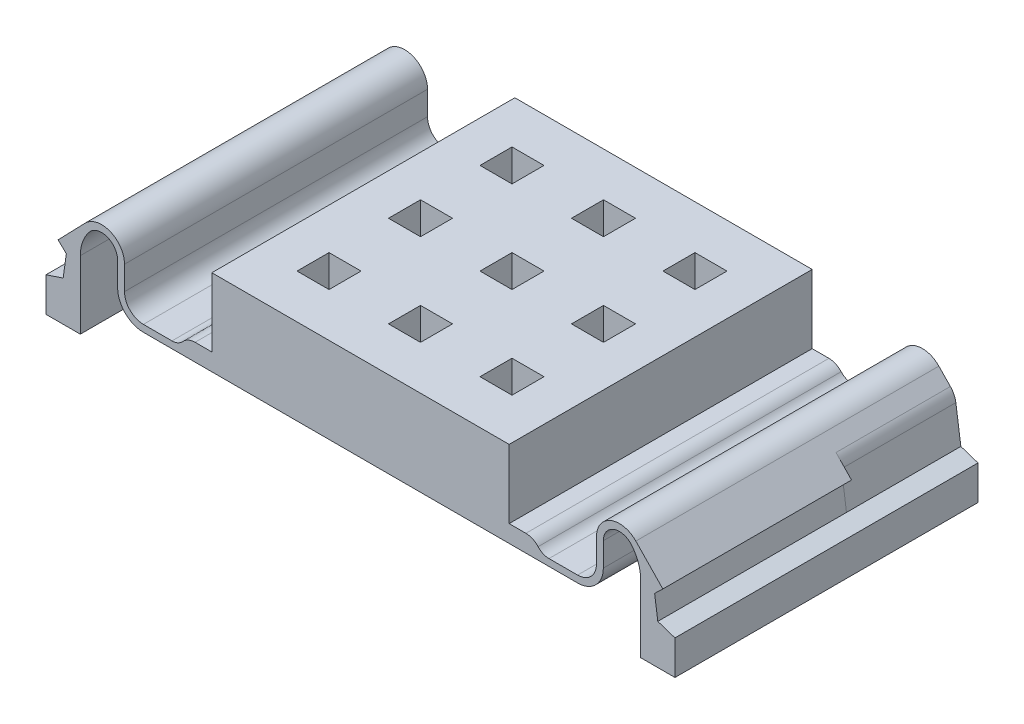
SolidWorks part; units mm, degrees
ref_plane "Plano frontal" through (0, 0, 0) normal (0, 0, 1) x (1, 0, 0)
ref_plane "Plano superior" through (0, 0, 0) normal (0, 1, 0) x (1, 0, 0)
ref_plane "Plano direito" through (0, 0, 0) normal (1, 0, 0) x (0, 0, -1)
sketch "Esboço3" plane through (0, 0, 0) normal (0, 0, 1) x (1, 0, 0)
  line L0 (35.3553, 11.1741) -> (52.3259, 28.1447) construction
  line L1 (-52.3259, 28.1447) -> (-35.3553, 11.1741) construction
  line L2 (-29.6985, 5.5172) -> (-26.0746, 1.8933) construction
  line L3 (-26.0746, 1.8933) -> (-24.9255, 9.9367) construction
  line L4 (-24.9255, 9.9367) -> (-25.1023, 10.1134) construction
  line L5 (-25.1023, 10.1134) -> (-29.6985, 5.5172) construction
  line L6 (25.1023, 10.1134) -> (24.9255, 9.9367) construction
  line L7 (24.9255, 9.9367) -> (26.0746, 1.8933) construction
  line L8 (26.0746, 1.8933) -> (29.6985, 5.5172) construction
  line L9 (29.6985, 5.5172) -> (25.1023, 10.1134) construction
  line L10 (63.1459, 37.2499) -> (26.001, 0) construction
  line L11 (-26.3397, 0.0372) -> (-63.4628, 37.1603) construction
  line L12 (26.3397, 0.0372) -> (24.9255, 9.9367) construction
  line L13 (-24.9255, 9.9367) -> (-26.3397, 0.0372) construction
  line L14 (18.9851, -0.6) -> (-18.9831, -0.6)
  line L15 (26.001, 0) -> (25.7227, 1.9805)
  line L16 (25.7227, 1.9805) -> (26.442, 2.6752)
  line L17 (26.442, 2.6752) -> (24.0804, 5.1207)
  line L18 (20.6376, 3.7297) -> (20.6376, 1.6525)
  line L19 (26.001, 0) -> (26.001, -1.5)
  line L20 (26.001, -1.5) -> (24.501, -1.5)
  line L21 (21.2376, 3.7297) -> (21.2376, 1.6525)
  line L22 (0.001, -0.6) -> (0.001, 0.9045) construction
  line L23 (24.501, -1.5) -> (24.501, 2.4453)
  line L24 (-7.2663, 0.9045) -> (7.2683, 0.9045)
  line L25 (18.9851, 0) -> (16.4851, 0)
  line L26 (0.001, -0.6) -> (18.9851, -0.6) construction
  line L27 (25.401, -0.042) -> (25.401, -1.5) construction
  line L28 (25.401, -0.042) -> (25.0859, 2.1998) construction
  line L29 (25.0859, 2.1998) -> (25.5936, 2.69) construction
  line L30 (25.5936, 2.69) -> (23.6488, 4.7039) construction
  line L31 (0.001, 0) -> (18.9851, 0) construction
  line L32 (7.2683, 0.9045) -> (14.4666, 0.9045)
  line L33 (-7.2663, 0.9045) -> (-14.4646, 0.9045)
  line L34 (-18.9831, 0) -> (-16.4831, 0)
  line L35 (-24.499, -1.5) -> (-24.499, 2.4453)
  line L36 (-21.2356, 3.7297) -> (-21.2356, 1.6525)
  line L37 (-25.999, -1.5) -> (-24.499, -1.5)
  line L38 (-25.999, 0) -> (-25.999, -1.5)
  line L39 (-20.6356, 3.7297) -> (-20.6356, 1.6525)
  line L40 (-26.44, 2.6752) -> (-24.0784, 5.1207)
  line L41 (-25.7207, 1.9805) -> (-26.44, 2.6752)
  line L42 (-25.999, 0) -> (-25.7207, 1.9805)
  arc A0 (24.0804, 5.1207) -> (20.6376, 3.7297) centre (22.64, 3.7297) ccw
  arc A1 (18.9851, 0) -> (20.6376, 1.6525) centre (18.9851, 1.6525) ccw
  arc A2 (18.9851, -0.6) -> (21.2376, 1.6525) centre (18.9851, 1.6525) ccw
  arc A3 (23.6488, 4.7039) -> (21.2376, 3.7297) centre (22.64, 3.7297) ccw
  arc A4 (24.501, 2.4453) -> (23.6488, 4.7039) centre (21.082, 2.4453) ccw
  arc A5 (16.4851, 0) -> (15.5348, 0.4259) centre (16.4851, 1.2733) cw
  arc A6 (15.5348, 0.4259) -> (14.4666, 0.9045) centre (14.4666, -0.5266) ccw
  arc A7 (-15.5328, 0.4259) -> (-14.4646, 0.9045) centre (-14.4646, -0.5266) cw
  arc A8 (-16.4831, 0) -> (-15.5328, 0.4259) centre (-16.4831, 1.2733) ccw
  arc A9 (-24.499, 2.4453) -> (-23.6468, 4.7039) centre (-21.08, 2.4453) cw
  arc A10 (-23.6468, 4.7039) -> (-21.2356, 3.7297) centre (-22.638, 3.7297) cw
  arc A11 (-18.9831, -0.6) -> (-21.2356, 1.6525) centre (-18.9831, 1.6525) cw
  arc A12 (-18.9831, 0) -> (-20.6356, 1.6525) centre (-18.9831, 1.6525) cw
  arc A13 (-24.0784, 5.1207) -> (-20.6356, 3.7297) centre (-22.638, 3.7297) cw
  dimension "D6" = 0.6
  dimension "D1" = 26
  dimension "D3" = 2
  dimension "D5" = 1
  dimension "D4" = 234
extrude "Ressalto-extrusão1" add sketch "Esboço3" along normal blind 16.5
sketch "Esboço4" plane through (0, -1.5, 0) normal (0, -1, 0) x (1, 0, 0)
  line L0 (24.501, 0) -> (26.001, 0) construction
  line L1 (26.001, 0) -> (26.001, 16.5) construction
  line L2 (26.001, 16.5) -> (24.501, 16.5) construction
  line L3 (24.501, 16.5) -> (24.501, 0) construction
  line L4 (-25.999, 0) -> (-24.499, 0) construction
  line L5 (-24.499, 0) -> (-24.499, 16.5) construction
  line L6 (-24.499, 16.5) -> (-25.999, 16.5) construction
  line L7 (-25.999, 16.5) -> (-25.999, 0) construction
  line L8 (24.501, 0) -> (26.001, 0)
  line L9 (26.001, 0) -> (26.001, 16.5)
  line L10 (26.001, 16.5) -> (24.501, 16.5)
  line L11 (24.501, 16.5) -> (24.501, 0)
  line L12 (-25.999, 0) -> (-24.499, 0)
  line L13 (-24.499, 0) -> (-24.499, 16.5)
  line L14 (-24.499, 16.5) -> (-25.999, 16.5)
  line L15 (-25.999, 16.5) -> (-25.999, 0)
extrude "Ressalto-extrusão2" add sketch "Esboço4" along normal blind 2
sketch "Esboço2" plane through (0, 0, 0) normal (0, 0, 1) x (1, 0, 0)
  line L0 (0.001, 0.9045) -> (0.001, -0.6) construction
  line L1 (14.4666, 0.9045) -> (-14.4646, 0.9045)
  line L2 (18.9851, -0.6) -> (-18.9831, -0.6)
  line L3 (-24.499, -3.5) -> (-25.999, -3.5)
  line L4 (-24.499, 2.4453) -> (-24.499, -3.5)
  line L5 (-21.2356, 1.6525) -> (-21.2356, 3.7297)
  line L6 (-18.9831, 0) -> (-16.4831, 0)
  line L7 (-20.6356, 3.7297) -> (-20.6356, 1.6525)
  line L8 (-25.0829, 4.0805) -> (-24.0784, 5.1207)
  line L9 (-25.999, -3.5) -> (-25.999, 0)
  line L10 (26.001, 0) -> (25.5647, 3.0972)
  line L11 (-25.999, 0) -> (-25.5627, 3.0972)
  line L39 (26.001, -3.5) -> (26.001, 0)
  line L40 (26.001, 0) -> (25.7227, 1.9805)
  line L41 (25.7227, 1.9805) -> (26.442, 2.6752)
  line L42 (26.442, 2.6752) -> (24.0804, 5.1207)
  line L43 (20.6376, 3.7297) -> (20.6376, 1.6525)
  line L44 (18.9851, 0) -> (16.4851, 0)
  line L45 (14.4666, 0.9045) -> (-14.4646, 0.9045)
  line L46 (-16.4831, 0) -> (-18.9831, 0)
  line L47 (-20.6356, 1.6525) -> (-20.6356, 3.7297)
  line L48 (-24.0784, 5.1207) -> (-26.44, 2.6752)
  line L49 (-26.44, 2.6752) -> (-25.7207, 1.9805)
  line L50 (-25.7207, 1.9805) -> (-25.999, 0)
  line L51 (-25.999, 0) -> (-25.999, -3.5)
  line L52 (-25.999, -3.5) -> (-24.499, -3.5)
  line L53 (-24.499, -3.5) -> (-24.499, 2.4453)
  line L54 (-21.2356, 3.7297) -> (-21.2356, 1.6525)
  line L55 (-18.9831, -0.6) -> (18.9851, -0.6)
  line L56 (21.2376, 1.6525) -> (21.2376, 3.7297)
  line L57 (24.501, 2.4453) -> (24.501, -3.5)
  line L58 (24.501, -3.5) -> (26.001, -3.5)
  line L59 (26.001, -3.5) -> (26.001, 0)
  line L62 (25.0849, 4.0805) -> (24.0804, 5.1207)
  line L63 (20.6376, 3.7297) -> (20.6376, 1.6525)
  line L64 (18.9851, 0) -> (16.4851, 0)
  line L76 (21.2376, 1.6525) -> (21.2376, 3.7297)
  line L77 (24.501, 2.4453) -> (24.501, -3.5)
  line L78 (24.501, -3.5) -> (26.001, -3.5)
  arc A0 (25.5647, 3.0972) -> (25.0849, 4.0805) centre (23.8109, 2.8501) ccw
  arc A1 (-24.499, 2.4453) -> (-23.6468, 4.7039) centre (-21.08, 2.4453) cw
  arc A2 (-23.6468, 4.7039) -> (-21.2356, 3.7297) centre (-22.638, 3.7297) cw
  arc A3 (-18.9831, -0.6) -> (-21.2356, 1.6525) centre (-18.9831, 1.6525) cw
  arc A4 (-15.5328, 0.4259) -> (-14.4646, 0.9045) centre (-14.4646, -0.5266) cw
  arc A5 (-15.5328, 0.4259) -> (-16.4831, 0) centre (-16.4831, 1.2733) cw
  arc A6 (-18.9831, 0) -> (-20.6356, 1.6525) centre (-18.9831, 1.6525) cw
  arc A7 (-24.0784, 5.1207) -> (-20.6356, 3.7297) centre (-22.638, 3.7297) cw
  arc A8 (-25.5627, 3.0972) -> (-25.0829, 4.0805) centre (-23.8089, 2.8501) cw
  arc A14 (24.0804, 5.1207) -> (20.6376, 3.7297) centre (22.64, 3.7297) ccw
  arc A15 (18.9851, 0) -> (20.6376, 1.6525) centre (18.9851, 1.6525) ccw
  arc A16 (15.5348, 0.4259) -> (16.4851, 0) centre (16.4851, 1.2733) ccw
  arc A17 (15.5348, 0.4259) -> (14.4666, 0.9045) centre (14.4666, -0.5266) ccw
  arc A18 (-14.4646, 0.9045) -> (-15.5328, 0.4259) centre (-14.4646, -0.5266) ccw
  arc A19 (-16.4831, 0) -> (-15.5328, 0.4259) centre (-16.4831, 1.2733) ccw
  arc A20 (-20.6356, 1.6525) -> (-18.9831, 0) centre (-18.9831, 1.6525) ccw
  arc A21 (-20.6356, 3.7297) -> (-24.0784, 5.1207) centre (-22.638, 3.7297) ccw
  arc A22 (-23.6468, 4.7039) -> (-24.499, 2.4453) centre (-21.08, 2.4453) ccw
  arc A23 (-21.2356, 3.7297) -> (-23.6468, 4.7039) centre (-22.638, 3.7297) ccw
  arc A24 (-21.2356, 1.6525) -> (-18.9831, -0.6) centre (-18.9831, 1.6525) ccw
  arc A25 (18.9851, -0.6) -> (21.2376, 1.6525) centre (18.9851, 1.6525) ccw
  arc A26 (23.6488, 4.7039) -> (21.2376, 3.7297) centre (22.64, 3.7297) ccw
  arc A27 (24.501, 2.4453) -> (23.6488, 4.7039) centre (21.082, 2.4453) ccw
  arc A28 (24.0804, 5.1207) -> (20.6376, 3.7297) centre (22.64, 3.7297) ccw
  arc A29 (18.9851, 0) -> (20.6376, 1.6525) centre (18.9851, 1.6525) ccw
  arc A30 (15.5348, 0.4259) -> (16.4851, 0) centre (16.4851, 1.2733) ccw
  arc A31 (15.5348, 0.4259) -> (14.4666, 0.9045) centre (14.4666, -0.5266) ccw
  arc A39 (18.9851, -0.6) -> (21.2376, 1.6525) centre (18.9851, 1.6525) ccw
  arc A40 (23.6488, 4.7039) -> (21.2376, 3.7297) centre (22.64, 3.7297) ccw
  arc A41 (24.501, 2.4453) -> (23.6488, 4.7039) centre (21.082, 2.4453) ccw
  dimension "D5" = 0
extrude "Ressalto-extrusão3" add sketch "Esboço2" against normal blind 10
sketch "Esboço5" plane through (0, 0.9045, 0) normal (0, 1, 0) x (1, 0, 0)
  line L0 (0.001, 10) -> (0.001, -16.5) construction
  line L1 (14.4666, 10) -> (-14.4646, 10) construction
  line L2 (14.4666, -16.5) -> (-14.4646, -16.5) construction
  line L4 (-12.999, 10) -> (13.001, 10)
  line L5 (-12.999, 10) -> (-12.999, -16.5)
  line L6 (-12.999, -16.5) -> (13.001, -16.5)
  line L7 (13.001, 10) -> (13.001, -16.5)
  line L8 (-12.999, 10) -> (13.001, -16.5) construction
  line L9 (-12.999, -16.5) -> (13.001, 10) construction
  point P6 (0.001, -3.25)
  dimension "D1" = 26.5
  dimension "D2" = 26
extrude "Ressalto-extrusão4" add sketch "Esboço5" along normal blind 6
sketch "Esboço6" plane through (0, -0.6, 0) normal (0, -1, 0) x (1, 0, 0)
  line L0 (0.001, -10) -> (0.001, 16.5) construction
  line L1 (-18.9831, -10) -> (18.9851, -10) construction
  line L2 (-18.9831, 16.5) -> (18.9851, 16.5) construction
  line L3 (0.001, 3.25) -> (-7.999, 3.25) construction
  line L4 (-7.999, 3.25) -> (-7.999, 11.25) construction
  line L5 (-1.399, 12.65) -> (1.401, 12.65)
  line L6 (-9.399, 12.65) -> (-6.599, 12.65)
  line L7 (-9.399, 12.65) -> (-9.399, 9.85)
  line L8 (-9.399, 9.85) -> (-6.599, 9.85)
  line L9 (-6.599, 12.65) -> (-6.599, 9.85)
  line L10 (-9.399, 12.65) -> (-6.599, 9.85) construction
  line L11 (-9.399, 9.85) -> (-6.599, 12.65) construction
  line L12 (-1.399, 12.65) -> (-1.399, 9.85)
  line L13 (-1.399, 9.85) -> (1.401, 9.85)
  line L14 (1.401, 12.65) -> (1.401, 9.85)
  line L15 (-1.399, 12.65) -> (1.401, 9.85) construction
  line L16 (-1.399, 9.85) -> (1.401, 12.65) construction
  line L17 (6.601, 12.65) -> (9.401, 12.65)
  line L18 (6.601, 12.65) -> (6.601, 9.85)
  line L19 (6.601, 9.85) -> (9.401, 9.85)
  line L20 (9.401, 12.65) -> (9.401, 9.85)
  line L21 (6.601, 12.65) -> (9.401, 9.85) construction
  line L22 (6.601, 9.85) -> (9.401, 12.65) construction
  line L23 (-1.399, 4.65) -> (1.401, 4.65)
  line L24 (-1.399, 4.65) -> (-1.399, 1.85)
  line L25 (-1.399, 1.85) -> (1.401, 1.85)
  line L26 (1.401, 4.65) -> (1.401, 1.85)
  line L27 (-1.399, 4.65) -> (1.401, 1.85) construction
  line L28 (-1.399, 1.85) -> (1.401, 4.65) construction
  line L29 (6.601, 4.65) -> (9.401, 4.65)
  line L30 (6.601, 4.65) -> (6.601, 1.85)
  line L31 (6.601, 1.85) -> (9.401, 1.85)
  line L32 (9.401, 4.65) -> (9.401, 1.85)
  line L33 (6.601, 4.65) -> (9.401, 1.85) construction
  line L34 (6.601, 1.85) -> (9.401, 4.65) construction
  line L35 (-1.399, -3.35) -> (1.401, -3.35)
  line L36 (-1.399, -3.35) -> (-1.399, -6.15)
  line L37 (-1.399, -6.15) -> (1.401, -6.15)
  line L38 (1.401, -3.35) -> (1.401, -6.15)
  line L39 (-1.399, -3.35) -> (1.401, -6.15) construction
  line L40 (-1.399, -6.15) -> (1.401, -3.35) construction
  line L41 (6.601, -3.35) -> (9.401, -3.35)
  line L42 (6.601, -3.35) -> (6.601, -6.15)
  line L43 (6.601, -6.15) -> (9.401, -6.15)
  line L44 (9.401, -3.35) -> (9.401, -6.15)
  line L45 (6.601, -3.35) -> (9.401, -6.15) construction
  line L46 (6.601, -6.15) -> (9.401, -3.35) construction
  line L47 (-9.399, 4.65) -> (-6.599, 4.65)
  line L48 (-9.399, 4.65) -> (-9.399, 1.85)
  line L49 (-9.399, 1.85) -> (-6.599, 1.85)
  line L50 (-6.599, 4.65) -> (-6.599, 1.85)
  line L51 (-9.399, 4.65) -> (-6.599, 1.85) construction
  line L52 (-9.399, 1.85) -> (-6.599, 4.65) construction
  line L53 (-9.399, -3.35) -> (-6.599, -3.35)
  line L54 (-9.399, -3.35) -> (-9.399, -6.15)
  line L55 (-9.399, -6.15) -> (-6.599, -6.15)
  line L56 (-6.599, -3.35) -> (-6.599, -6.15)
  line L57 (-9.399, -3.35) -> (-6.599, -6.15) construction
  line L58 (-9.399, -6.15) -> (-6.599, -3.35) construction
  dimension "D1" = 8
  dimension "D2" = 8
  dimension "D3" = 2.8
  dimension "D4" = 2.8
  dimension "D5" = 3
  dimension "D6" = 3
extrude "Corte-extrusão1" cut sketch "Esboço6" against normal through all
sketch "Esboço8" plane through (0, 0, 16.5) normal (0, 0, 1) x (1, 0, 0)
  line L0 (-25.999, -3.5) -> (-27.499, -3.5)
  line L1 (-27.499, -3.5) -> (-27.499, -0.5)
  line L2 (-27.499, -0.5) -> (-25.999, 0)
  line L3 (-25.999, 0) -> (-25.999, -3.5)
  line L4 (0.001, -0.6) -> (0.001, 6.9045) construction
  line L5 (-18.9831, -0.6) -> (18.9851, -0.6) construction
  line L6 (-12.999, 6.9045) -> (13.001, 6.9045) construction
  line L7 (26.001, 0) -> (26.001, -3.5)
  line L8 (27.501, -0.5) -> (26.001, 0)
  line L9 (27.501, -3.5) -> (27.501, -0.5)
  line L10 (26.001, -3.5) -> (27.501, -3.5)
extrude "Ressalto-extrusão5" add sketch "Esboço8" against normal through all
